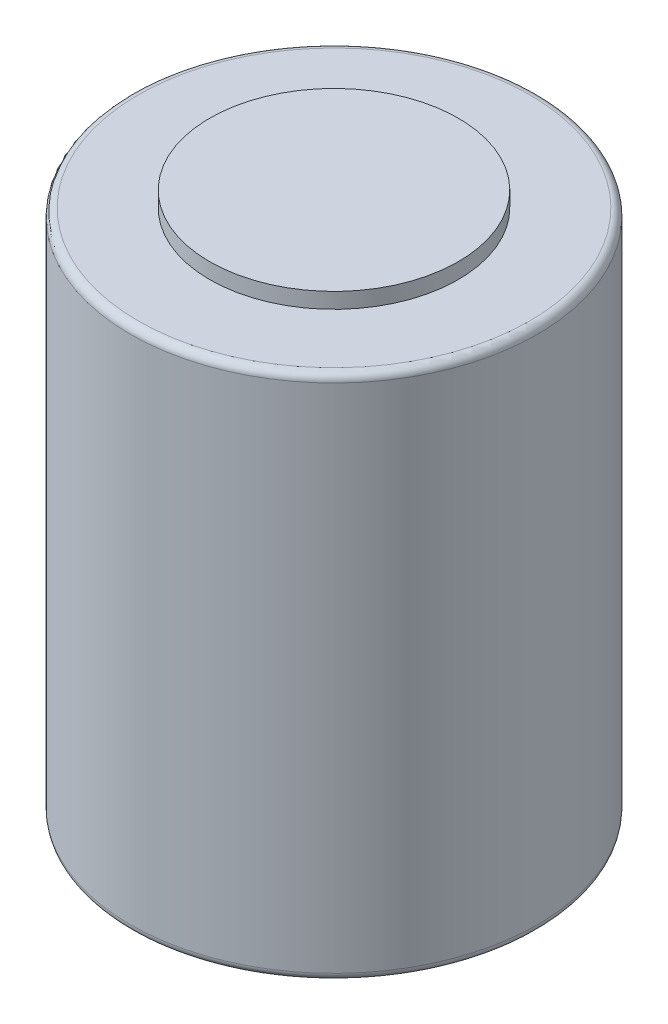
SolidWorks part; units mm, degrees
ref_plane "Спереди" through (0, 0, 0) normal (0, 0, 1) x (1, 0, 0)
ref_plane "Сверху" through (0, 0, 0) normal (0, 1, 0) x (1, 0, 0)
ref_plane "Справа" through (0, 0, 0) normal (1, 0, 0) x (0, 0, -1)
sketch "Эскиз1" plane through (0, 0, 0) normal (0, 1, 0) x (1, 0, 0)
  circle A0 centre (0, 0) radius 13.1
  dimension "D1" = 26.2
extrude "Бобышка-Вытянуть1" add sketch "Эскиз1" along normal blind 35
sketch "Эскиз2" plane through (0, 35, 0) normal (0, 1, 0) x (1, 0, 0)
  circle A0 centre (0, 0) radius 8
  circle A1 centre (0, 0) radius 19.2707
  dimension "D1" = 16
extrude "Вырез-Вытянуть1" cut sketch "Эскиз2" against normal blind 1
sketch "Эскиз3" plane through (0, 0, 0) normal (0, -1, 0) x (1, 0, 0)
  circle A0 centre (0, 0) radius 17.551
  circle A1 centre (0, 0) radius 10.25
  dimension "D1" = 20.5
extrude "Вырез-Вытянуть2" cut sketch "Эскиз3" against normal blind 0.1
fillet "Скругление1" radius 0.5 2 edges at (0, 34, 13.1) (0, 0.1, -13.1)
